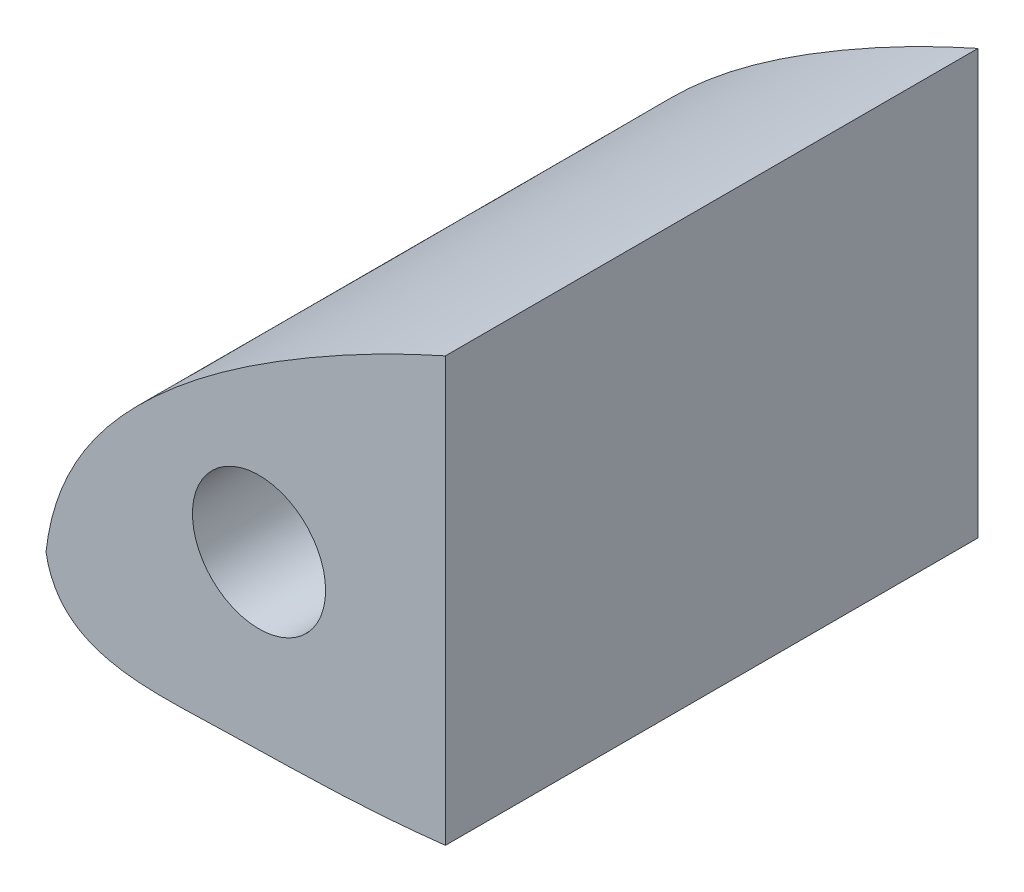
SolidWorks part; units mm, degrees
ref_plane "Front Plane" through (0, 0, 0) normal (0, 0, 1) x (1, 0, 0)
ref_plane "Top Plane" through (0, 0, 0) normal (0, 1, 0) x (1, 0, 0)
ref_plane "Right Plane" through (0, 0, 0) normal (1, 0, 0) x (0, 0, -1)
sketch "Sketch1" plane through (0, 0, 0) normal (0, 0, 1) x (1, 0, 0)
  spline S0 degree 3 poles (0.0006, 0.0001) (0.8106, 7.3592) (8.6491, 17.8566) (26.2867, 29.9752) (52.1111, 42.0692) (89.5976, 49.2908) (131.4008, 47.8848) (173.2567, 40.0411) (217.9611, 29.613) (256.9521, 19.5289) (290.3598, 8.711) (301.2732, 4.3828) (314.8169, -0.5162) (309.8463, 0.0001) knots 0 0 0 0 0.060864 0.113688 0.188609 0.312909 0.448482 0.557612 0.691544 0.852438 0.929756 0.976058 1 1 1 1
  spline S1 degree 3 poles (309.8463, 0.0001) (303.9568, 1.471) (293.9895, 2.094) (276.264, 4.5144) (260.8463, 5.4274) (235.8588, 7.8703) (205.1014, 8.8381) (157.7186, 9.0307) (110.4973, 6.1815) (66.5062, -0.5867) (36.4547, -6.0985) (15.3166, -6.1891) (1.2307, -6.9241) (0.0006, 0.0001) knots 0 0 0 0 0.057787 0.095275 0.171021 0.205339 0.335319 0.464904 0.658702 0.785512 0.893517 0.943092 1 1 1 1
extrude "Boss-Extrude1" add sketch "Sketch1" along normal blind 50.8
sketch "Sketch2" plane through (0, 0, 50.8) normal (0, 0, 1) x (1, 0, 0)
  circle A0 centre (20.32, 10.16) radius 6.35
  circle A1 centre (227.2963, 19.0501) radius 3.175
  dimension "D2" = 12.7
  dimension "D3" = 6.35
  dimension "D6" = 20.32
  dimension "D1" = 82.55
  dimension "D4" = 19.05
  dimension "D5" = 10.16
extrude "Cut-Extrude1" cut sketch "Sketch2" against normal through all
sketch "Sketch3" plane through (0, 0, 50.8) normal (0, 0, 1) x (1, 0, 0)
  line L1 (38.1, 71.718) -> (331.2889, 71.718)
  line L2 (38.1, 71.718) -> (38.1, -66.2532)
  line L3 (38.1, -66.2532) -> (331.2889, -66.2532)
  line L4 (331.2889, 71.718) -> (331.2889, -66.2532)
  dimension "D1" = 38.1
extrude "Cut-Extrude2" cut sketch "Sketch3" against normal through all
